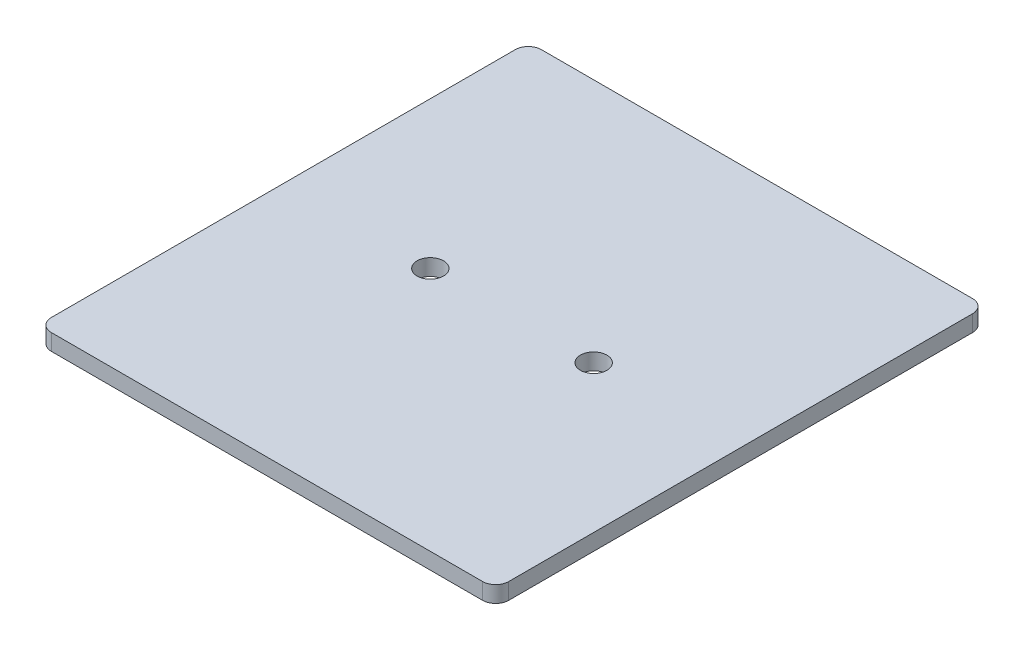
SolidWorks part; units mm, degrees
ref_plane "Front Plane" through (0, 0, 0) normal (0, 0, 1) x (1, 0, 0)
ref_plane "Top Plane" through (0, 0, 0) normal (0, 1, 0) x (1, 0, 0)
ref_plane "Right Plane" through (0, 0, 0) normal (1, 0, 0) x (0, 0, -1)
sketch "Sketch1" plane through (0, 0, 0) normal (0, 1, 0) x (1, 0, 0)
  line L1 (-70, 75) -> (70, 75)
  line L2 (-70, 75) -> (-70, -75)
  line L3 (-70, -75) -> (70, -75)
  line L4 (70, 75) -> (70, -75)
  line L5 (-70, 75) -> (70, -75) construction
  line L6 (-70, -75) -> (70, 75) construction
  point P0 (0, 0)
  dimension "D1" = 150
  dimension "D2" = 140
extrude "Boss-Extrude1" add sketch "Sketch1" along normal blind 5
sketch "Sketch2" plane through (0, 5, 0) normal (0, 1, 0) x (1, 0, 0)
  line L0 (-70, 0) -> (70, 0) construction
  line L1 (-70, 75) -> (-70, -75) construction
  line L2 (70, -75) -> (70, 75) construction
  circle A0 centre (-25, 0) radius 4.05
  dimension "D1" = 8.1
  dimension "D2" = 25
extrude "Cut-Extrude1" cut sketch "Sketch2" against normal through all
mirror "Mirror1" about plane through (0, 0, 0) normal (1, 0, 0) of "Cut-Extrude1"
fillet "Fillet1" radius 4 4 edges at (-70, 2.5, -75) (-70, 2.5, 75) (70, 2.5, -75) (70, 2.5, 75)
